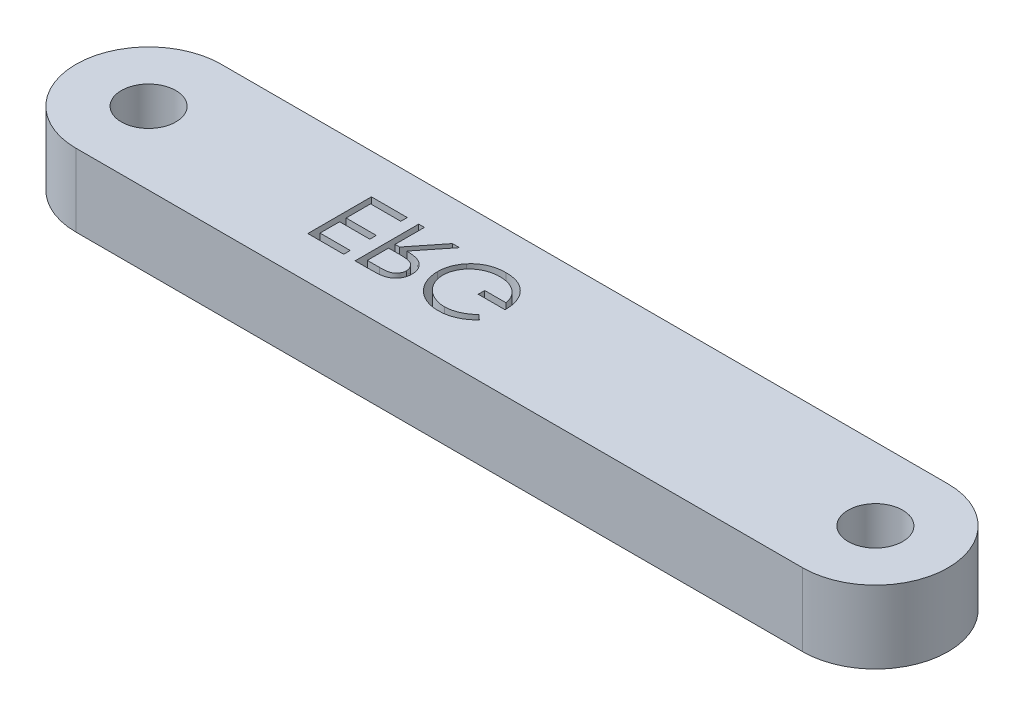
SolidWorks part; units mm, degrees
ref_plane "Front Plane" through (0, 0, 0) normal (0, 0, 1) x (1, 0, 0)
ref_plane "Top Plane" through (0, 0, 0) normal (0, 1, 0) x (1, 0, 0)
ref_plane "Right Plane" through (0, 0, 0) normal (1, 0, 0) x (0, 0, -1)
sketch "Sketch2" plane through (0, 0, 0) normal (0, 1, 0) x (1, 0, 0)
  line L0 (0, 0) -> (400, 0) construction
  line L1 (0, 40) -> (400, 40)
  line L2 (0, -40) -> (400, -40)
  arc A0 (0, 40) -> (0, -40) centre (0, 0) ccw
  arc A1 (400, -40) -> (400, 40) centre (400, 0) ccw
  circle A2 centre (0, 0) radius 15
  circle A3 centre (400, 0) radius 15
  point P3 (200, 0)
  dimension "D3" = 30
  dimension "D1" = 400
  dimension "D2" = 80
extrude "Boss-Extrude1" add sketch "Sketch2" along normal mid plane 40
sketch "Sketch3" plane through (0, -20, 0) normal (0, -1, 0) x (1, 0, 0)
  line L0 (0, 0) -> (100, 0) construction
  line L1 (100, 0) -> (254.9748, 0) construction
  line L2 (100, 0) -> (100, -18.1391) construction
  line L3 (100, -18.1391) -> (262.4232, -18.1391) construction
  text T0 "ERG" font "Century Gothic" height 35
  point P5 (100, -21.0649)
  point P8 (0, 0)
  point P9 (100, -12.9378)
  point P10 (100, -20.4147)
  point P11 (0, 0)
  point P12 (0, 0)
  point P13 (0, 0)
  point P14 (100, -12.2876)
  point P15 (100, -20.4147)
  point P16 (100, -18.1391)
  point P17 (0, 0)
  dimension "D1" = 100
extrude "Cut-Extrude1" cut sketch "Sketch3" against normal through all
